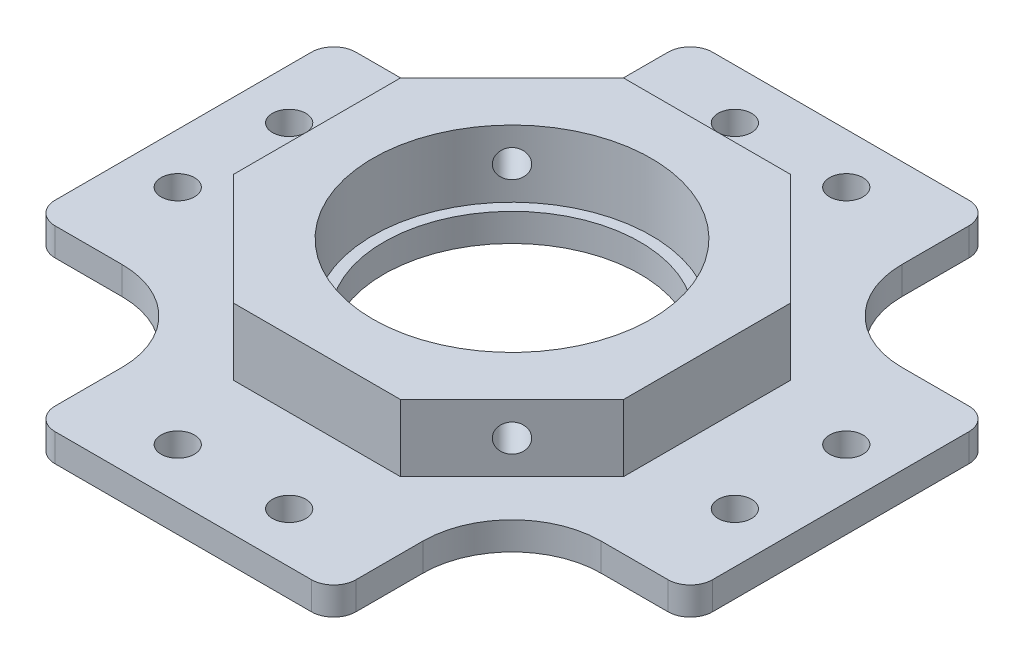
SolidWorks part; units mm, degrees
ref_plane "前视基准面" through (0, 0, 0) normal (0, 0, 1) x (1, 0, 0)
ref_plane "上视基准面" through (0, 0, 0) normal (0, 1, 0) x (1, 0, 0)
ref_plane "右视基准面" through (0, 0, 0) normal (1, 0, 0) x (0, 0, -1)
sketch "草图1" plane through (0, 0, 0) normal (0, 1, 0) x (1, 0, 0)
  line L0 (0, 0) -> (0, 27003.4302) construction
  line L1 (0, 0) -> (27003.4302, 0) construction
  line L2 (-11.5, 29.5) -> (11.5, 29.5)
  line L3 (-11.5, -29.5) -> (11.5, -29.5)
  line L4 (-29.5, 11.5) -> (-29.5, -11.5)
  line L5 (29.5, 11.5) -> (29.5, -11.5)
  line L6 (-13.5, 27.5) -> (-13.5, 21.5)
  line L7 (-21.5, 13.5) -> (-27.5, 13.5)
  line L8 (21.5, 13.5) -> (27.5, 13.5)
  line L9 (13.5, 27.5) -> (13.5, 21.5)
  line L10 (-21.5, -13.5) -> (-27.5, -13.5)
  line L11 (-13.5, -27.5) -> (-13.5, -21.5)
  line L12 (13.5, -27.5) -> (13.5, -21.5)
  line L13 (21.5, -13.5) -> (27.5, -13.5)
  circle A0 centre (0, 0) radius 11.5
  circle A1 centre (-5, 25) radius 1.5
  circle A2 centre (5, 25) radius 1.5
  arc A3 (-21.5, -13.5) -> (-13.5, -21.5) centre (-21.5, -21.5) cw
  arc A4 (13.5, -21.5) -> (21.5, -13.5) centre (21.5, -21.5) cw
  arc A5 (21.5, 13.5) -> (13.5, 21.5) centre (21.5, 21.5) cw
  arc A6 (-13.5, 21.5) -> (-21.5, 13.5) centre (-21.5, 21.5) cw
  arc A7 (11.5, -29.5) -> (13.5, -27.5) centre (11.5, -27.5) ccw
  arc A8 (-11.5, -29.5) -> (-13.5, -27.5) centre (-11.5, -27.5) cw
  arc A9 (-29.5, -11.5) -> (-27.5, -13.5) centre (-27.5, -11.5) ccw
  arc A10 (-29.5, 11.5) -> (-27.5, 13.5) centre (-27.5, 11.5) cw
  arc A11 (13.5, 27.5) -> (11.5, 29.5) centre (11.5, 27.5) ccw
  arc A12 (-11.5, 29.5) -> (-13.5, 27.5) centre (-11.5, 27.5) ccw
  arc A13 (29.5, -11.5) -> (27.5, -13.5) centre (27.5, -11.5) cw
  arc A14 (29.5, 11.5) -> (27.5, 13.5) centre (27.5, 11.5) ccw
  circle A15 centre (25, 5) radius 1.5
  circle A16 centre (25, -5) radius 1.5
  circle A17 centre (5, -25) radius 1.5
  circle A18 centre (-5, -25) radius 1.5
  circle A19 centre (-25, -5) radius 1.5
  circle A20 centre (-25, 5) radius 1.5
  point P25 (-13.5, -13.5)
  point P28 (13.5, -13.5)
  point P31 (13.5, 13.5)
  point P34 (-13.5, 13.5)
  point P37 (13.5, -29.5)
  point P40 (-13.5, -29.5)
  point P43 (-29.5, -13.5)
  point P46 (-29.5, 13.5)
  point P49 (13.5, 29.5)
  point P52 (-13.5, 29.5)
  point P55 (29.5, -13.5)
  point P58 (29.5, 13.5)
  point P59 (26.1052, 6.6669)
  point P60 (0, 0)
  point P74 (0, 0)
  dimension "D3" = 23
  dimension "D4" = 3
  dimension "D5" = 3
  dimension "D6" = 7
  dimension "D7" = 8
  dimension "D8" = 2
  dimension "D1" = 27
  dimension "D2" = 16
  dimension "D9" = 4
extrude "凸台-拉伸1" add sketch "草图1" along normal blind 2.5
sketch "草图2" plane through (0, 2.5, 0) normal (0, 1, 0) x (1, 0, 0)
  line L0 (17.5, 7.5) -> (7.5, 17.5)
  line L1 (7.5, -17.5) -> (-7.5, -17.5)
  line L2 (17.5, -7.5) -> (17.5, 7.5)
  line L3 (7.5, 17.5) -> (-7.5, 17.5)
  line L4 (-17.5, -7.5) -> (-17.5, 7.5)
  line L5 (17.5, -17.5) -> (-17.5, 17.5) construction
  line L6 (17.5, 17.5) -> (-17.5, -17.5) construction
  line L8 (-17.5, 7.5) -> (-7.5, 17.5)
  line L9 (-7.5, -17.5) -> (-17.5, -7.5)
  line L10 (17.5, -7.5) -> (7.5, -17.5)
  circle A2 centre (0, 0) radius 12.5
  point P0 (0, 0)
  point P7 (0, 0)
  point P15 (-17.5, 17.5)
  point P20 (13.9871, 7.5)
  dimension "D1" = 25
  dimension "D2" = 5
extrude "凸台-拉伸2" add sketch "草图2" along normal blind 6
hole_wizard "M3 螺纹孔1" positions "3D草图1" profile "草图3" tap size "M3" standard "GB"
sketch3d "3D草图1"
  line L0 (-12.5, 5.5, 12.5) -> (-12.5, 8.5, 12.5) construction
  line L1 (-17.5, 8.5, 7.5) -> (-7.5, 8.5, 17.5) construction
  point P0 (-12.5, 5.5, 12.5)
  dimension "D1" = 3
sketch "草图3" plane through (-12.5, 5.5, 12.5) normal (0, 1, 0) x (0.7071, 0, 0.7071)
  line L0 (0, 0) -> (0, 5.1777)
  line L1 (0, 5.1777) -> (1.25, 5.1777)
  line L2 (1.25, 5.1777) -> (1.25, 0)
  line L5 (1.25, 0) -> (0, 0)
  line L11 (0, -6.35) -> (0, 107.95) construction
  dimension "通孔螺纹孔钻头直径" = 2.5
  dimension "通孔螺纹孔钻头深度" = 5.1777
cosmetic thread "孔螺蚊线1" parameters "D2"=3
pattern_circular "阵列(圆周)1" count 4 over 360 about axis through (0, 8.5, 0) along (0, -1, 0) of "M3 螺纹孔1"
cosmetic thread "孔螺蚊线2" parameters "D2"=3
cosmetic thread "孔螺蚊线3" parameters "D2"=3
cosmetic thread "孔螺蚊线4" parameters "D2"=3
